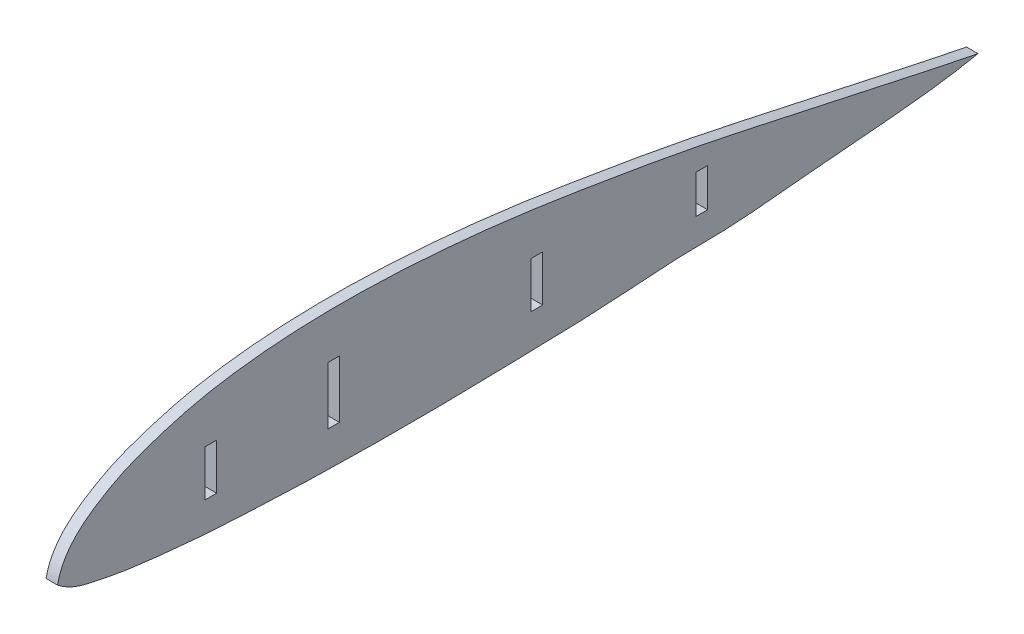
SolidWorks part; units mm, degrees
ref_plane "Спереди" through (0, 0, 0) normal (0, 0, 1) x (1, 0, 0)
ref_plane "Сверху" through (0, 0, 0) normal (0, 1, 0) x (1, 0, 0)
ref_plane "Справа" through (0, 0, 0) normal (1, 0, 0) x (0, 0, -1)
sketch "Эскиз1" plane through (0, 0, 0) normal (1, 0, 0) x (0, 0, -1)
  spline S0 degree 3 poles (-240, 0) (-238.5396, 6.886) (-231.612, 12.3378) (-222.1753, 17.4121) (-214.1119, 20.3435) (-204.1561, 23.2639) (-188.1046, 25.8933) (-168.0072, 26.9601) (-143.9456, 26.0264) (-119.9183, 23.5678) (-95.9538, 19.7588) (-71.9127, 15.562) (-48.006, 10.2206) (-23.9898, 5.1714) (-8.0375, 1.5236) (0, 0) knots 0 0 0 0 0.075346 0.102328 0.12789 0.177564 0.226025 0.321727 0.4173 0.513305 0.60992 0.706974 0.804635 0.902346 1 1 1 1
  spline S1 degree 3 poles (-240, 0) (-236.5239, -2.8866) (-230.2208, -4.0678) (-222.0286, -5.6488) (-214.0096, -6.6085) (-204.0195, -7.6506) (-188.0105, -8.621) (-168.0084, -9.355) (-143.9974, -9.5447) (-119.9964, -9.0006) (-95.9841, -8.4523) (-79.4445, -6.8615) (-63.4129, -6.9414) (-47.4215, -5.1493) (-23.952, -3.3462) (-7.916, -1.6722) (0, 0) knots 0 0 0 0 0.053475 0.078709 0.103753 0.153673 0.203448 0.302856 0.402199 0.501554 0.600955 0.70043 0.70748 0.799996 0.899716 1 1 1 1
  point P0 (-240, 0)
  point P1 (-234, 9.888)
  point P2 (-228, 14.16)
  point P3 (-222, 17.316)
  point P4 (-216, 19.608)
  point P5 (-204, 23.04)
  point P6 (-192, 25.104)
  point P7 (-168, 26.592)
  point P8 (-144, 25.776)
  point P9 (-120, 23.352)
  point P10 (-96, 19.704)
  point P11 (-72, 15.384)
  point P12 (-48, 10.272)
  point P13 (-24, 5.1)
  point P14 (-12, 2.46)
  point P15 (0, 0)
  point P16 (-234, -3.12)
  point P17 (-228, -4.5)
  point P18 (-222, -5.58)
  point P19 (-216, -6.36)
  point P20 (-204, -7.5648)
  point P21 (-192, -8.3472)
  point P22 (-168, -9.24)
  point P23 (-144, -9.4224)
  point P24 (-120, -9)
  point P25 (-96, -8.16)
  point P26 (-72, -6.9024)
  point P27 (-48, -5.34)
  point P28 (-24, -3.24)
  point P29 (-12, -1.98)
extrude "Бобышка-Вытянуть1" add sketch "Эскиз1" along normal blind 3
sketch "Эскиз2" plane through (0, 0, 0) normal (-1, 0, 0) x (0, 0, 1)
  line L0 (116.5, 0) -> (116.5, 12)
  line L2 (116.5, 12) -> (113.5, 12)
  line L7 (201.5, 0) -> (198.5, 0)
  line L8 (116.5, 0) -> (113.5, 0)
  line L9 (113.5, 12) -> (113.5, 0)
  line L10 (198.5, 0) -> (198.5, 12)
  line L11 (198.5, 12) -> (201.5, 12)
  line L12 (201.5, 12) -> (201.5, 0)
  line L13 (169.5, 0) -> (169.5, 15)
  line L14 (169.5, 15) -> (166.5, 15)
  line L15 (166.5, 0) -> (169.5, 0)
  line L16 (166.5, 15) -> (166.5, 0)
  line L17 (70.5, 0) -> (70.5, 10)
  line L18 (70.5, 0) -> (73.5, 0)
  line L19 (70.5, 10) -> (73.5, 10)
  line L20 (73.5, 10) -> (73.5, 0)
extrude "Вырез-Вытянуть1" cut sketch "Эскиз2" against normal blind 3
